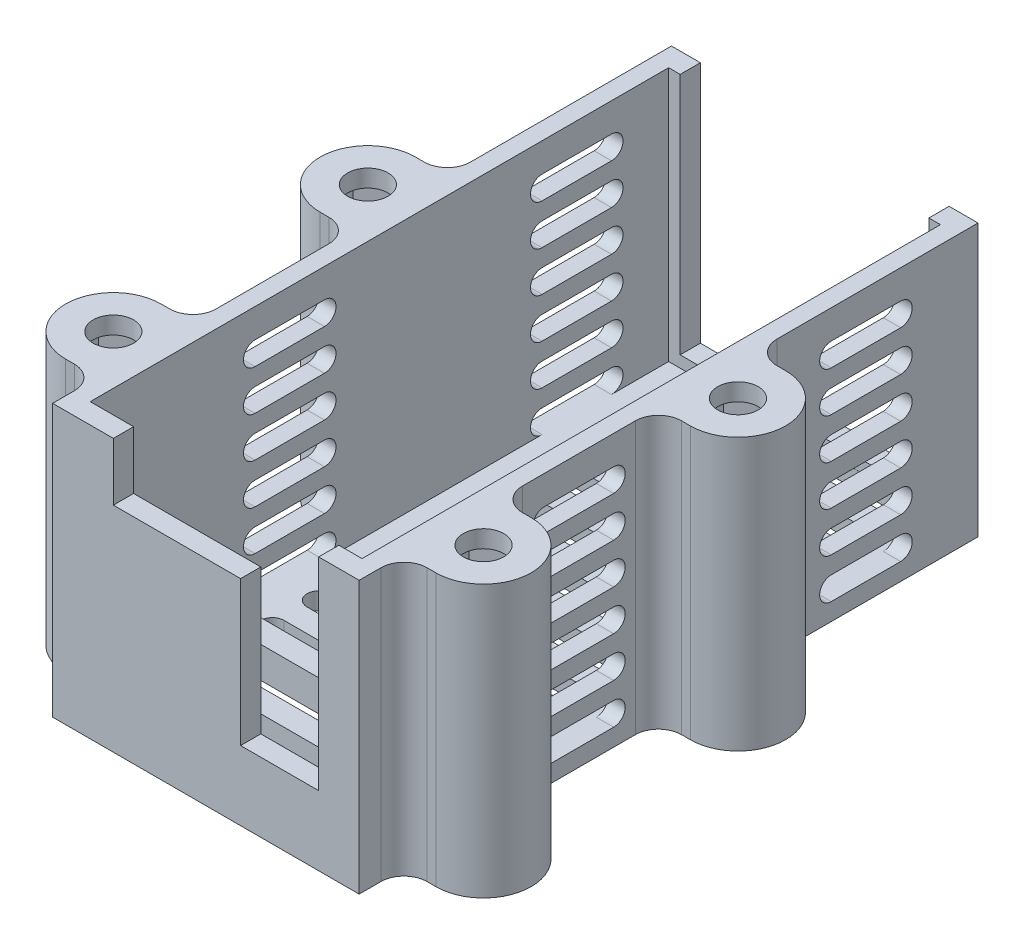
SolidWorks part; units mm, degrees
ref_plane "Front Plane" through (0, 0, 0) normal (0, 0, 1) x (1, 0, 0)
ref_plane "Top Plane" through (0, 0, 0) normal (0, 1, 0) x (1, 0, 0)
ref_plane "Right Plane" through (0, 0, 0) normal (1, 0, 0) x (0, 0, -1)
sketch "Sketch1" plane through (0, 0, 0) normal (0, 1, 0) x (1, 0, 0)
  line L0 (0, 26.75) -> (0, -26.75) construction
  line L1 (-11.75, 25.25) -> (11.75, 25.25)
  line L2 (-11.75, 25.25) -> (-11.75, -25.25)
  line L3 (-11.75, -25.25) -> (11.75, -25.25)
  line L4 (11.75, 25.25) -> (11.75, -25.25)
  line L5 (-11.75, 25.25) -> (11.75, -25.25) construction
  line L6 (-11.75, -25.25) -> (11.75, 25.25) construction
  line L7 (13.25, 26.75) -> (-13.25, 26.75)
  line L8 (13.25, 26.75) -> (13.25, -26.75)
  line L9 (13.25, -26.75) -> (-13.25, -26.75)
  line L10 (-13.25, 26.75) -> (-13.25, -26.75)
  line L11 (13.25, 26.75) -> (-13.25, -26.75) construction
  line L12 (13.25, -26.75) -> (-13.25, 26.75) construction
  line L13 (-16, -14.625) -> (-13.25, -14.625)
  line L14 (-16, -22.875) -> (-13.25, -22.875)
  line L15 (-16, -0.875) -> (-13.25, -0.875)
  line L16 (-16, 7.375) -> (-13.25, 7.375)
  line L17 (16, -22.875) -> (13.25, -22.875)
  line L18 (16, -14.625) -> (13.25, -14.625)
  line L19 (16, -0.875) -> (13.25, -0.875)
  line L20 (16, 7.375) -> (13.25, 7.375)
  circle A0 centre (-16, -18.75) radius 1.75
  circle A1 centre (-16, -18.75) radius 4.125
  circle A2 centre (-16, 3.25) radius 1.75
  circle A3 centre (-16, 3.25) radius 4.125
  circle A4 centre (16, -18.75) radius 1.75
  circle A5 centre (16, -18.75) radius 4.125
  circle A6 centre (16, 3.25) radius 1.75
  circle A7 centre (16, 3.25) radius 4.125
  point P0 (0, 0)
  point P6 (0, 0)
  dimension "D5" = 8.25
  dimension "D6" = 3.5
  dimension "D1" = 23.5
  dimension "D2" = 50.5
  dimension "D3" = 1.5
  dimension "D4" = 1.5
  dimension "D7" = 32
  dimension "D8" = 6.5
  dimension "D10" = 22
  dimension "D9" = 2
extrude "Boss-Extrude2" add sketch "Sketch1" along normal blind 1.5 contours L4 L1 L2 L3 | L8 A7 L7 L10 A3 A1 L9 A5 L1 L4 L3 L2 | L10 A3 | L10 A1 | A5 L8 | A7 L8 | L19 A7 L8 | A7 L8 A6 | L8 A7 L20 | L8 A5 L18 | A5 L8 A4 | L17 A5 L8 | A1 L10 L13 | A1 L10 A0 | A1 L14 L10 | A3 L10 L16 | A3 L10 A2 | A3 L15 L10
sketch "Sketch2" plane through (0, 1.5, 0) normal (0, 1, 0) x (1, 0, 0)
  line L1 (11.75, 25.0026) -> (-11.75, 25.0026)
  line L2 (11.75, 25.0026) -> (11.75, -25.0026)
  line L3 (11.75, -25.0026) -> (-11.75, -25.0026)
  line L4 (-11.75, 25.0026) -> (-11.75, -25.0026)
  line L5 (11.75, 25.0026) -> (-11.75, -25.0026) construction
  line L6 (11.75, -25.0026) -> (-11.75, 25.0026) construction
  line L16 (16, -14.625) -> (13.25, -14.625)
  line L17 (13.25, -14.625) -> (13.25, -0.875)
  line L18 (13.25, -0.875) -> (16, -0.875)
  line L19 (16, 7.375) -> (13.25, 7.375)
  line L20 (13.25, 7.375) -> (13.25, 26.75)
  line L21 (13.25, 26.75) -> (-13.25, 26.75)
  line L22 (13.25, 26.75) -> (-13.25, 26.75)
  line L23 (-13.25, 26.75) -> (-13.25, 7.375)
  line L24 (-13.25, 26.75) -> (-13.25, 7.375)
  line L25 (-13.25, 7.375) -> (-16, 7.375)
  line L26 (-13.25, 7.375) -> (-16, 7.375)
  line L27 (-16, -0.875) -> (-13.25, -0.875)
  line L28 (-16, -0.875) -> (-13.25, -0.875)
  line L29 (-13.25, -0.875) -> (-13.25, -14.625)
  line L30 (13.25, -26.75) -> (13.25, -22.875)
  line L31 (13.25, -22.875) -> (16, -22.875)
  line L32 (16, -14.625) -> (13.25, -14.625)
  line L33 (13.25, -14.625) -> (13.25, -0.875)
  line L34 (13.25, -0.875) -> (16, -0.875)
  line L35 (16, 7.375) -> (13.25, 7.375)
  line L36 (13.25, 7.375) -> (13.25, 26.75)
  line L37 (-13.25, -0.875) -> (-13.25, -14.625)
  line L44 (-13.25, -14.625) -> (-16, -14.625)
  line L45 (-13.25, -14.625) -> (-16, -14.625)
  line L46 (13.25, -26.75) -> (13.25, -22.875)
  line L47 (13.25, -22.875) -> (16, -22.875)
  line L48 (-16, -22.875) -> (-13.25, -22.875)
  line L49 (-16, -22.875) -> (-13.25, -22.875)
  line L50 (-13.25, -22.875) -> (-13.25, -26.75)
  line L51 (-13.25, -22.875) -> (-13.25, -26.75)
  line L52 (-13.25, -26.75) -> (13.25, -26.75)
  line L53 (-13.25, -26.75) -> (13.25, -26.75)
  circle A0 centre (-16, 3.25) radius 1.75 construction
  circle A1 centre (-16, -18.75) radius 1.75 construction
  circle A2 centre (16, -18.75) radius 1.75 construction
  circle A3 centre (16, 3.25) radius 1.75 construction
  arc A4 (16, -22.875) -> (16, -14.625) centre (16, -18.75) ccw
  arc A5 (16, -0.875) -> (16, 7.375) centre (16, 3.25) ccw
  arc A6 (-16, 7.375) -> (-16, -0.875) centre (-16, 3.25) ccw
  arc A7 (-16, 7.375) -> (-16, -0.875) centre (-16, 3.25) ccw
  arc A8 (16, -22.875) -> (16, -14.625) centre (16, -18.75) ccw
  arc A9 (16, -0.875) -> (16, 7.375) centre (16, 3.25) ccw
  arc A10 (-16, -14.625) -> (-16, -22.875) centre (-16, -18.75) ccw
  arc A11 (-16, -14.625) -> (-16, -22.875) centre (-16, -18.75) ccw
  circle A12 centre (-16, 3.25) radius 1.75
  circle A13 centre (-16, -18.75) radius 1.75
  circle A14 centre (16, -18.75) radius 1.75
  circle A15 centre (16, 3.25) radius 1.75
  point P0 (0, 0)
  dimension "D3" = 1.5
  dimension "D1" = 0
extrude "Boss-Extrude3" add sketch "Sketch2" along normal blind 22
sketch "Sketch3" plane through (0, 23.5, 0) normal (0, 1, 0) x (1, 0, 0)
  line L0 (13.25, 26.75) -> (-13.25, 26.75) construction
  line L1 (-10.75, 26.75) -> (10.75, 26.75)
  line L2 (-10.75, 26.75) -> (-10.75, 25.0026)
  line L3 (-10.75, 25.0026) -> (10.75, 25.0026)
  line L4 (10.75, 26.75) -> (10.75, 25.0026)
  line L5 (11.75, 25.0026) -> (-11.75, 25.0026) construction
  line L6 (-11.75, 25.0026) -> (-11.75, -25.0026) construction
  line L7 (11.75, -25.0026) -> (11.75, 25.0026) construction
  dimension "D1" = 1
  dimension "D2" = 1
extrude "Cut-Extrude1" cut sketch "Sketch3" against normal offset from surface (21 mm away) 1
sketch "Sketch4" plane through (0, 0, 26.75) normal (0, 0, 1) x (1, 0, 0)
  line L0 (11.75, 23.5) -> (11.75, 0) construction
  line L1 (-13.25, 23.5) -> (13.25, 23.5) construction
  line L2 (13.25, 0) -> (-13.25, 0) construction
  line L3 (-11.75, 23.5) -> (-11.75, 0) construction
  line L4 (11.75, 1.5) -> (-11.75, 1.5) construction
  line L5 (9.75, 6) -> (3, 6)
  line L6 (9.75, 6) -> (9.75, 23.5)
  line L7 (9.75, 23.5) -> (3, 23.5)
  line L8 (3, 6) -> (3, 23.5)
  line L9 (-13.25, 1.5) -> (13.25, 1.5) construction
  line L10 (-13.25, 23.5) -> (-13.25, 0) construction
  line L11 (13.25, 23.5) -> (13.25, 0) construction
  line L12 (0, 23.5) -> (0, 0) construction
  line L13 (-8, 21.5) -> (-8, 23.5)
  line L14 (-8, 21.5) -> (8, 21.5)
  line L15 (-8, 21.5) -> (-8, 18.5)
  line L16 (-8, 18.5) -> (8, 18.5)
  line L17 (8, 21.5) -> (8, 18.5)
  line L18 (-8, 21.5) -> (8, 18.5) construction
  line L19 (-8, 18.5) -> (8, 21.5) construction
  line L20 (8, 21.5) -> (8, 23.5)
  point P25 (0, 20)
  line M3 (13.25, 23.5) -> (-13.25, 23.5)
  dimension "D1" = 2
  dimension "D2" = 6.75
  dimension "D3" = 4.5
  dimension "D4" = 16
  dimension "D5" = 14
  dimension "D6" = 3
extrude "Cut-Extrude2" cut sketch "Sketch4" against normal up to next contours L13 L14 L8 M3 | L14 L20 L7 L8 | L20 L17 L16 L8 L5 L6 M3 | L17 L14 L8 L16 | L15 L16 L8 L14
sketch "Sketch5" plane through (0, 0, 0) normal (0, -1, 0) x (1, 0, 0)
  line L1 (-16, 15.2859) -> (-13, 17.0179)
  line L2 (-13, 17.0179) -> (-13, 20.4821)
  line L3 (-13, 20.4821) -> (-16, 22.2141)
  line L4 (-16, 22.2141) -> (-19, 20.4821)
  line L5 (-19, 20.4821) -> (-19, 17.0179)
  line L6 (-19, 17.0179) -> (-16, 15.2859)
  line L7 (16, 15.2859) -> (19, 17.0179)
  line L8 (19, 17.0179) -> (19, 20.4821)
  line L9 (19, 20.4821) -> (16, 22.2141)
  line L10 (16, 22.2141) -> (13, 20.4821)
  line L11 (13, 20.4821) -> (13, 17.0179)
  line L12 (13, 17.0179) -> (16, 15.2859)
  line L13 (16, -6.7141) -> (19, -4.9821)
  line L14 (19, -4.9821) -> (19, -1.5179)
  line L15 (19, -1.5179) -> (16, 0.2141)
  line L16 (16, 0.2141) -> (13, -1.5179)
  line L17 (13, -1.5179) -> (13, -4.9821)
  line L18 (13, -4.9821) -> (16, -6.7141)
  line L19 (-16, -6.7141) -> (-13, -4.9821)
  line L20 (-13, -4.9821) -> (-13, -1.5179)
  line L21 (-13, -1.5179) -> (-16, 0.2141)
  line L22 (-16, 0.2141) -> (-19, -1.5179)
  line L23 (-19, -1.5179) -> (-19, -4.9821)
  line L24 (-19, -4.9821) -> (-16, -6.7141)
  circle A0 centre (-16, 18.75) radius 3 construction
  circle A1 centre (16, 18.75) radius 3 construction
  circle A2 centre (16, -3.25) radius 3 construction
  circle A3 centre (-16, -3.25) radius 3 construction
  dimension "D1" = 6
extrude "Cut-Extrude3" cut sketch "Sketch5" against normal offset from surface (22 mm away) 1.5 up to face at (-16, 23.5, -1.5)
sketch "Sketch6" plane through (0, 0, 0) normal (0, -1, 0) x (1, 0, 0)
  line L0 (0, 26.75) -> (0, -26.75) construction
  line L1 (13.25, 26.75) -> (-13.25, 26.75) construction
  line L2 (13.25, -26.75) -> (-13.25, -26.75) construction
  line L3 (-9, 0) -> (9, 0) construction
  line L4 (-9, 1) -> (9, 1)
  line L5 (-9, -1) -> (9, -1)
  line L6 (-9, 4) -> (9, 4) construction
  line L7 (-9, 5) -> (9, 5)
  line L8 (-9, 3) -> (9, 3)
  line L9 (-9, 8) -> (9, 8) construction
  line L10 (-9, 9) -> (9, 9)
  line L11 (-9, 7) -> (9, 7)
  line L12 (-9, 12) -> (9, 12) construction
  line L13 (-9, 13) -> (9, 13)
  line L14 (-9, 11) -> (9, 11)
  line L15 (-9, 16) -> (9, 16) construction
  line L16 (-9, 17) -> (9, 17)
  line L17 (-9, 15) -> (9, 15)
  line L18 (-9, 20) -> (9, 20) construction
  line L19 (-9, 21) -> (9, 21)
  line L20 (-9, 19) -> (9, 19)
  line L21 (-9, 24) -> (9, 24) construction
  line L22 (-9, 25) -> (9, 25)
  line L23 (-9, 23) -> (9, 23)
  line L24 (-13.25, 0) -> (13.25, 0) construction
  line L25 (-13.25, -26.75) -> (-13.25, -7.375) construction
  line L26 (13.25, -26.75) -> (13.25, -7.375) construction
  line L27 (-9, -4) -> (9, -4) construction
  line L28 (-9, -5) -> (9, -5)
  line L29 (-9, -3) -> (9, -3)
  line L30 (-9, -8) -> (9, -8) construction
  line L31 (-9, -9) -> (9, -9)
  line L32 (-9, -7) -> (9, -7)
  line L33 (-9, -12) -> (9, -12) construction
  line L34 (-9, -13) -> (9, -13)
  line L35 (-9, -11) -> (9, -11)
  line L36 (-9, -16) -> (9, -16) construction
  line L37 (-9, -17) -> (9, -17)
  line L38 (-9, -15) -> (9, -15)
  line L39 (-9, -20) -> (9, -20) construction
  line L40 (-9, -21) -> (9, -21)
  line L41 (-9, -19) -> (9, -19)
  line L42 (-9, -24) -> (9, -24) construction
  line L43 (-9, -25) -> (9, -25)
  line L44 (-9, -23) -> (9, -23)
  arc A0 (-9, 1) -> (-9, -1) centre (-9, 0) ccw
  arc A1 (9, -1) -> (9, 1) centre (9, 0) ccw
  arc A2 (-9, 5) -> (-9, 3) centre (-9, 4) ccw
  arc A3 (9, 3) -> (9, 5) centre (9, 4) ccw
  arc A4 (-9, 9) -> (-9, 7) centre (-9, 8) ccw
  arc A5 (9, 7) -> (9, 9) centre (9, 8) ccw
  arc A6 (-9, 13) -> (-9, 11) centre (-9, 12) ccw
  arc A7 (9, 11) -> (9, 13) centre (9, 12) ccw
  arc A8 (-9, 17) -> (-9, 15) centre (-9, 16) ccw
  arc A9 (9, 15) -> (9, 17) centre (9, 16) ccw
  arc A10 (-9, 21) -> (-9, 19) centre (-9, 20) ccw
  arc A11 (9, 19) -> (9, 21) centre (9, 20) ccw
  arc A12 (-9, 25) -> (-9, 23) centre (-9, 24) ccw
  arc A13 (9, 23) -> (9, 25) centre (9, 24) ccw
  arc A14 (-9, -5) -> (-9, -3) centre (-9, -4) cw
  arc A15 (9, -3) -> (9, -5) centre (9, -4) cw
  arc A16 (-9, -9) -> (-9, -7) centre (-9, -8) cw
  arc A17 (9, -7) -> (9, -9) centre (9, -8) cw
  arc A18 (-9, -13) -> (-9, -11) centre (-9, -12) cw
  arc A19 (9, -11) -> (9, -13) centre (9, -12) cw
  arc A20 (-9, -17) -> (-9, -15) centre (-9, -16) cw
  arc A21 (9, -15) -> (9, -17) centre (9, -16) cw
  arc A22 (-9, -21) -> (-9, -19) centre (-9, -20) cw
  arc A23 (9, -19) -> (9, -21) centre (9, -20) cw
  arc A24 (-9, -25) -> (-9, -23) centre (-9, -24) cw
  arc A25 (9, -23) -> (9, -25) centre (9, -24) cw
  point P8 (0, 0)
  point P18 (0, 4)
  point P25 (0, 8)
  point P32 (0, 12)
  point P39 (0, 16)
  point P46 (0, 20)
  point P53 (0, 24)
  point P64 (0, -4)
  point P71 (0, -8)
  point P78 (0, -12)
  point P85 (0, -16)
  point P92 (0, -20)
  point P99 (0, -24)
  dimension "D1" = 18
  dimension "D2" = 2
  dimension "D4" = 4
  dimension "D3" = 7
extrude "Cut-Extrude4" cut sketch "Sketch6" against normal up to next
sketch "Sketch7" plane through (0, 1.5, 0) normal (0, 1, 0) x (1, 0, 0)
  line L0 (-11.75, 25.0026) -> (-11.75, -25.0026) construction
  line L1 (-11.75, -13) -> (11.75, -13)
  line L2 (-11.75, -13) -> (-11.75, -15)
  line L3 (-11.75, -15) -> (11.75, -15)
  line L4 (11.75, -13) -> (11.75, -15)
  line L7 (11.75, -25.0026) -> (11.75, 25.0026) construction
  line L9 (-9, -15) -> (9, -15) construction
  line L10 (9, -13) -> (-9, -13) construction
extrude "Boss-Extrude4" add sketch "Sketch7" along normal blind 1.2
sketch "Sketch8" plane through (13.25, 0, 0) normal (1, 0, 0) x (0, 0, -1)
  line L0 (-7.75, 23.5) -> (-7.75, 0) construction
  line L1 (-14.625, 23.5) -> (-0.875, 23.5) construction
  line L2 (-0.875, 0) -> (-14.625, 0) construction
  line L3 (17.0625, 23.5) -> (17.0625, 0) construction
  line L4 (7.375, 23.5) -> (26.75, 23.5) construction
  line L5 (26.75, 0) -> (7.375, 0) construction
  line L6 (-26.75, 2.5) -> (26.75, 2.5) construction
  line L7 (-26.75, 23.5) -> (-26.75, 0) construction
  line L8 (26.75, 23.5) -> (26.75, 0) construction
  line L9 (-10.75, 2.5) -> (-4.75, 2.5) construction
  line L10 (-10.75, 3.5) -> (-4.75, 3.5)
  line L11 (-10.75, 1.5) -> (-4.75, 1.5)
  line L12 (14.0625, 2.5) -> (20.0625, 2.5) construction
  line L13 (14.0625, 3.5) -> (20.0625, 3.5)
  line L14 (14.0625, 1.5) -> (20.0625, 1.5)
  line L17 (-10.75, 6) -> (-4.75, 6) construction
  line L18 (-10.75, 7) -> (-4.75, 7)
  line L19 (-10.75, 5) -> (-4.75, 5)
  line L20 (14.0625, 6) -> (20.0625, 6) construction
  line L21 (14.0625, 7) -> (20.0625, 7)
  line L22 (14.0625, 5) -> (20.0625, 5)
  line L23 (-10.75, 9.5) -> (-4.75, 9.5) construction
  line L24 (-10.75, 10.5) -> (-4.75, 10.5)
  line L25 (-10.75, 8.5) -> (-4.75, 8.5)
  line L26 (14.0625, 9.5) -> (20.0625, 9.5) construction
  line L27 (14.0625, 10.5) -> (20.0625, 10.5)
  line L28 (14.0625, 8.5) -> (20.0625, 8.5)
  line L29 (-10.75, 13) -> (-4.75, 13) construction
  line L30 (-10.75, 14) -> (-4.75, 14)
  line L31 (-10.75, 12) -> (-4.75, 12)
  line L32 (14.0625, 13) -> (20.0625, 13) construction
  line L33 (14.0625, 14) -> (20.0625, 14)
  line L34 (14.0625, 12) -> (20.0625, 12)
  line L35 (-10.75, 16.5) -> (-4.75, 16.5) construction
  line L36 (-10.75, 17.5) -> (-4.75, 17.5)
  line L37 (-10.75, 15.5) -> (-4.75, 15.5)
  line L38 (14.0625, 16.5) -> (20.0625, 16.5) construction
  line L39 (14.0625, 17.5) -> (20.0625, 17.5)
  line L40 (14.0625, 15.5) -> (20.0625, 15.5)
  line L41 (-10.75, 20) -> (-4.75, 20) construction
  line L42 (-10.75, 21) -> (-4.75, 21)
  line L43 (-10.75, 19) -> (-4.75, 19)
  line L44 (14.0625, 20) -> (20.0625, 20) construction
  line L45 (14.0625, 21) -> (20.0625, 21)
  line L46 (14.0625, 19) -> (20.0625, 19)
  arc A0 (-10.75, 3.5) -> (-10.75, 1.5) centre (-10.75, 2.5) ccw
  arc A1 (-4.75, 1.5) -> (-4.75, 3.5) centre (-4.75, 2.5) ccw
  arc A2 (14.0625, 3.5) -> (14.0625, 1.5) centre (14.0625, 2.5) ccw
  arc A3 (20.0625, 1.5) -> (20.0625, 3.5) centre (20.0625, 2.5) ccw
  arc A4 (-10.75, 7) -> (-10.75, 5) centre (-10.75, 6) ccw
  arc A5 (-4.75, 5) -> (-4.75, 7) centre (-4.75, 6) ccw
  arc A6 (14.0625, 7) -> (14.0625, 5) centre (14.0625, 6) ccw
  arc A7 (20.0625, 5) -> (20.0625, 7) centre (20.0625, 6) ccw
  arc A8 (-10.75, 10.5) -> (-10.75, 8.5) centre (-10.75, 9.5) ccw
  arc A9 (-4.75, 8.5) -> (-4.75, 10.5) centre (-4.75, 9.5) ccw
  arc A10 (14.0625, 10.5) -> (14.0625, 8.5) centre (14.0625, 9.5) ccw
  arc A11 (20.0625, 8.5) -> (20.0625, 10.5) centre (20.0625, 9.5) ccw
  arc A12 (-10.75, 14) -> (-10.75, 12) centre (-10.75, 13) ccw
  arc A13 (-4.75, 12) -> (-4.75, 14) centre (-4.75, 13) ccw
  arc A14 (14.0625, 14) -> (14.0625, 12) centre (14.0625, 13) ccw
  arc A15 (20.0625, 12) -> (20.0625, 14) centre (20.0625, 13) ccw
  arc A16 (-10.75, 17.5) -> (-10.75, 15.5) centre (-10.75, 16.5) ccw
  arc A17 (-4.75, 15.5) -> (-4.75, 17.5) centre (-4.75, 16.5) ccw
  arc A18 (14.0625, 17.5) -> (14.0625, 15.5) centre (14.0625, 16.5) ccw
  arc A19 (20.0625, 15.5) -> (20.0625, 17.5) centre (20.0625, 16.5) ccw
  arc A20 (-10.75, 21) -> (-10.75, 19) centre (-10.75, 20) ccw
  arc A21 (-4.75, 19) -> (-4.75, 21) centre (-4.75, 20) ccw
  arc A22 (14.0625, 21) -> (14.0625, 19) centre (14.0625, 20) ccw
  arc A23 (20.0625, 19) -> (20.0625, 21) centre (20.0625, 20) ccw
  point P20 (-7.75, 2.5)
  point P27 (17.0625, 2.5)
  point P39 (-7.75, 6)
  point P46 (17.0625, 6)
  point P53 (-7.75, 9.5)
  point P60 (17.0625, 9.5)
  point P67 (-7.75, 13)
  point P74 (17.0625, 13)
  point P81 (-7.75, 16.5)
  point P88 (17.0625, 16.5)
  point P95 (-7.75, 20)
  point P102 (17.0625, 20)
  dimension "D1" = 2.5
  dimension "D2" = 2
  dimension "D3" = 2
  dimension "D4" = 6
  dimension "D5" = 6
  dimension "D7" = 3.5
  dimension "D6" = 6
extrude "Cut-Extrude5" cut sketch "Sketch8" against normal up to surface (26.5 mm away) up to face at (-13.25, 11.75, -17.0625)
fillet "Fillet1" radius 2 8 edges at (-13.25, 11.75, 14.625) (-13.25, 11.75, 22.875) (-13.25, 11.75, 0.875) (-13.25, 11.75, -7.375) (13.25, 11.75, -7.375) (13.25, 11.75, 14.625) (13.25, 11.75, 22.875) (13.25, 11.75, 0.875)
